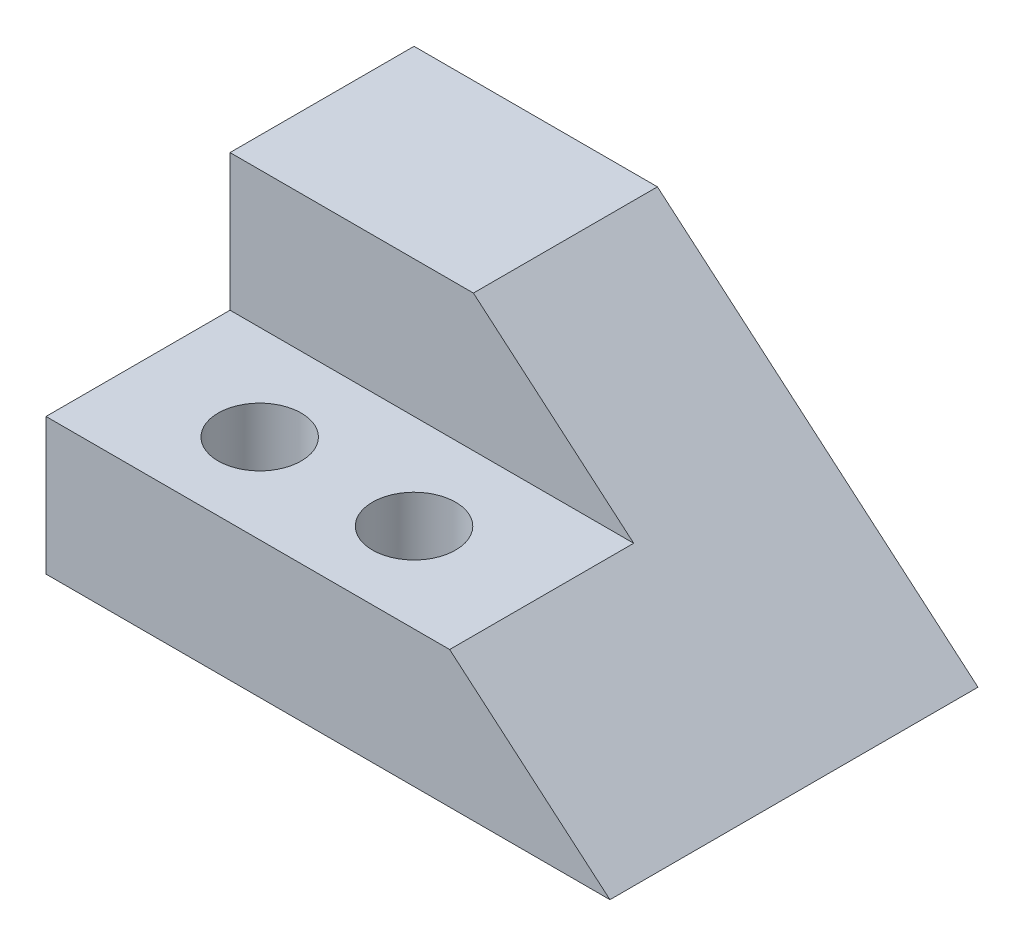
SolidWorks part; units mm, degrees
ref_plane "정면" through (0, 0, 0) normal (0, 0, 1) x (1, 0, 0)
ref_plane "윗면" through (0, 0, 0) normal (0, 1, 0) x (1, 0, 0)
ref_plane "우측면" through (0, 0, 0) normal (1, 0, 0) x (0, 0, -1)
sketch "스케치1" plane through (0, 0, 0) normal (0, 0, 1) x (1, 0, 0)
  line L0 (0, 0) -> (95, 0)
  line L1 (95, 0) -> (41, 46)
  line L2 (41, 46) -> (0, 46)
  line L3 (0, 46) -> (0, 0)
  dimension "D1" = 46
  dimension "D2" = 41
  dimension "D3" = 95
extrude "보스-돌출1" add sketch "스케치1" against normal blind 62
sketch "스케치2" plane through (0, 0, 0) normal (-1, 0, 0) x (0, 0, 1)
  line L1 (0, 46) -> (-31, 46)
  line L2 (0, 46) -> (0, 23)
  line L3 (0, 23) -> (-31, 23)
  line L4 (-31, 46) -> (-31, 23)
  dimension "D1" = 31
  dimension "D2" = 23
extrude "컷-돌출1" cut sketch "스케치2" against normal blind 70
sketch "스케치3" plane through (0, 23, 0) normal (0, 1, 0) x (1, 0, 0)
  line L0 (0, 31) -> (0, 0) construction
  line L1 (0, 0) -> (68, 0) construction
  circle A0 centre (21, 15) radius 7
  circle A1 centre (47, 15) radius 7
  point P8 (47, 15)
  dimension "D4" = 14
  dimension "D5" = 15
  dimension "D1" = 21
  dimension "D2" = 26
  dimension "D3" = 15
extrude "컷-돌출2" cut sketch "스케치3" against normal blind 62
